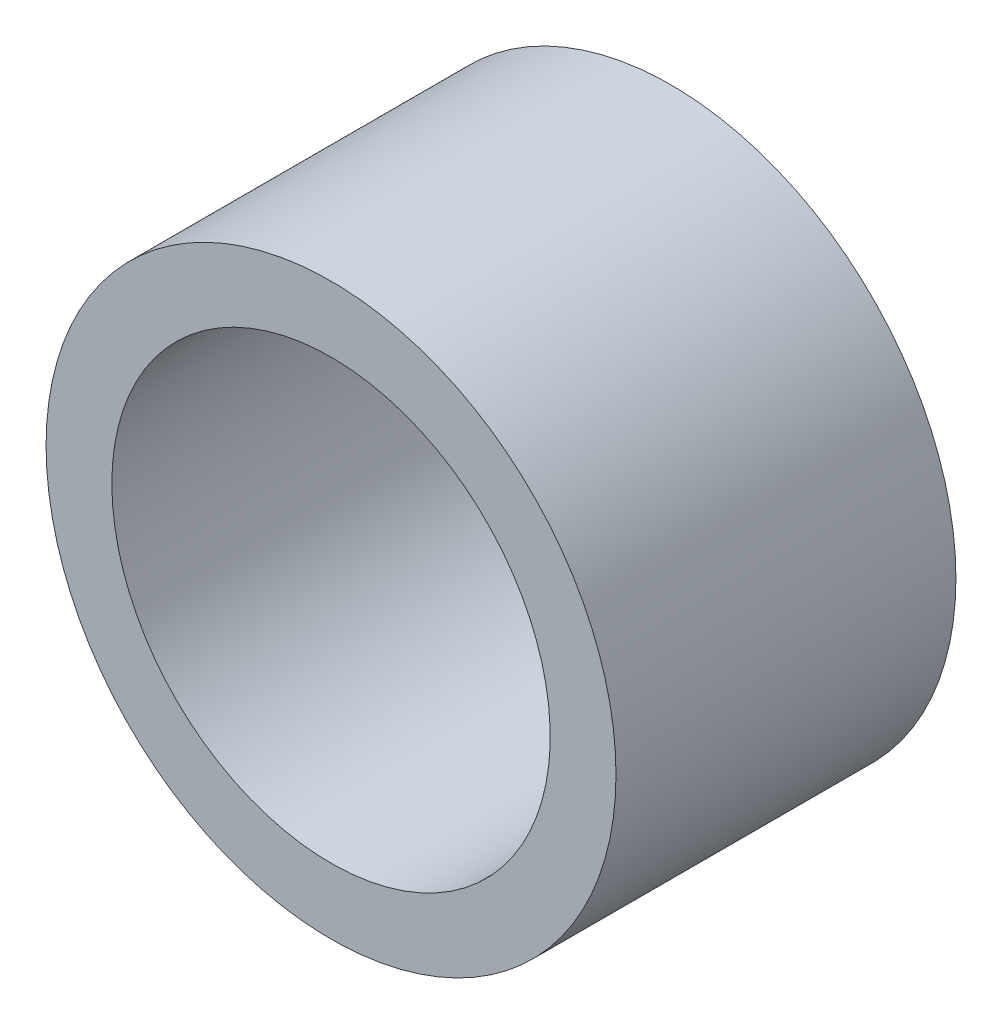
SolidWorks part; units mm, degrees
ref_plane "Front Plane" through (0, 0, 0) normal (1, 0, 0) x (0, 1, 0)
ref_plane "Top Plane" through (0, 0, 0) normal (0, 0, 1) x (0, 1, 0)
ref_plane "Right Plane" through (0, 0, 0) normal (0, 1, 0) x (-1, 0, 0)
sketch "Sketch2" plane through (0, 0, 0) normal (1, 0, 0) x (0, 1, 0)
  line L0 (-63.5, 0) -> (-82.55, 0)
  line L5 (-82.55, 0) -> (-82.55, 98.4738)
  line L6 (-82.55, 98.4738) -> (-63.5, 98.4738)
  line L7 (-63.5, 98.4738) -> (-63.5, 0)
  line L8 (0, 0) -> (0, 98.4738) construction
  point P3 (-96.378, 0)
  dimension "D1" = 63.5
  dimension "D2" = 82.55
revolve "Revolve1" add sketch "Sketch2" angle 360 about L8
